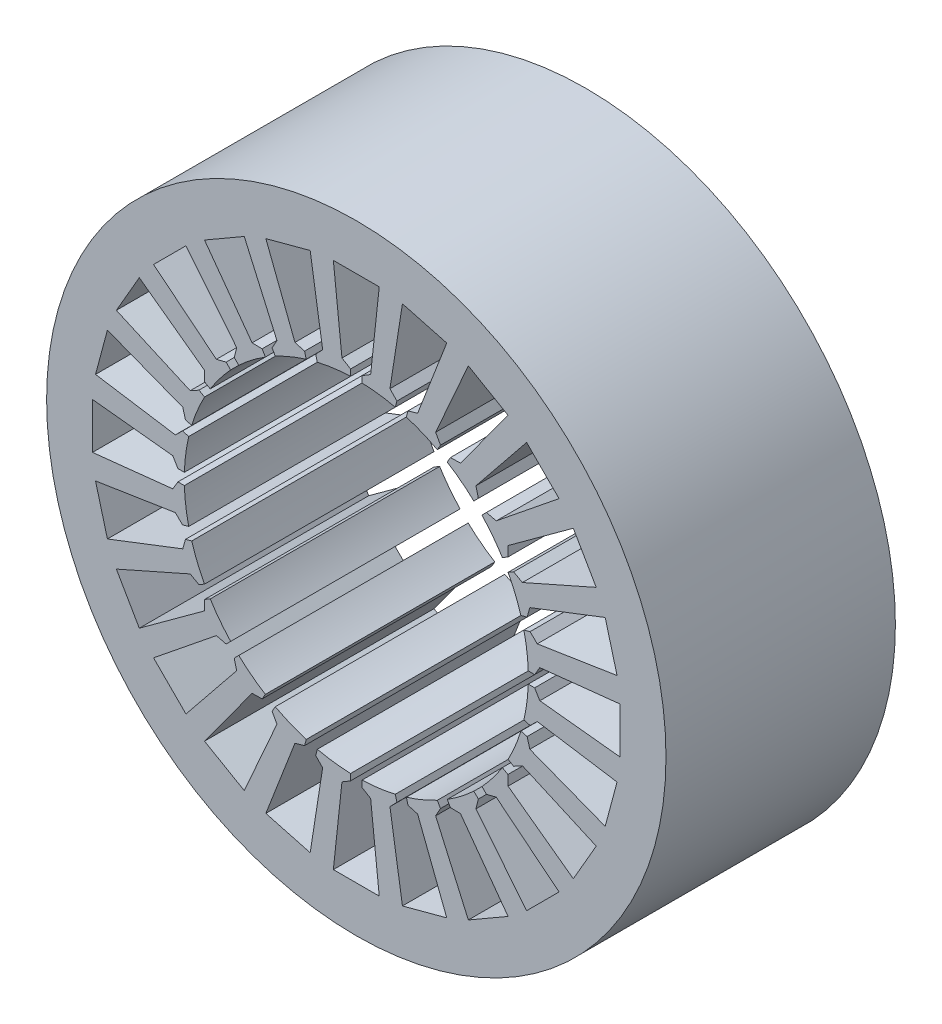
SolidWorks part; units mm, degrees
ref_plane "Спереди" through (0, 0, 0) normal (0, 0, 1) x (1, 0, 0)
ref_plane "Сверху" through (0, 0, 0) normal (0, 1, 0) x (1, 0, 0)
ref_plane "Справа" through (0, 0, 0) normal (1, 0, 0) x (0, 0, -1)
sketch "Эскиз1" plane through (0, 0, 0) normal (0, 0, 1) x (1, 0, 0)
  circle A0 centre (0, 0) radius 54
  circle A1 centre (0, 0) radius 30
extrude "Stator_stack" add sketch "Эскиз1" along normal blind 40 from offset 20
sketch "Эскиз2" plane through (0, 0, 0) normal (0, 0, 1) x (1, 0, 0)
  line L0 (28.9828, -1) -> (31.1, -1)
  line L1 (31.1, -1) -> (32, -2.5)
  line L2 (32, -2.5) -> (39.5, -3.3036)
  line L3 (39.5, -3.3036) -> (46, -4)
  line L4 (46, -4) -> (46, 4)
  line L5 (46, 4) -> (39.5, 3.3036)
  line L6 (39.5, 3.3036) -> (32, 2.5)
  line L7 (32, 2.5) -> (31.1, 1)
  line L8 (31.1, 1) -> (28.9828, 1)
  line L9 (28.9828, 1) -> (28.9828, -1)
  line L10 (28.254, 6.5354) -> (30.2991, 7.0833)
  line L11 (30.2991, 7.0833) -> (31.5567, 5.8674)
  line L12 (31.5567, 5.8674) -> (39.0091, 7.0323)
  line L13 (39.0091, 7.0323) -> (45.4679, 8.042)
  line L14 (45.4679, 8.042) -> (43.3973, 15.7694)
  line L15 (43.3973, 15.7694) -> (37.299, 13.4144)
  line L16 (37.299, 13.4144) -> (30.2626, 10.697)
  line L17 (30.2626, 10.697) -> (29.7815, 9.0152)
  line L18 (29.7815, 9.0152) -> (27.7364, 8.4672)
  line L19 (27.7364, 8.4672) -> (28.254, 6.5354)
  line L20 (25.5998, 13.6254) -> (27.4334, 14.684)
  line L21 (27.4334, 14.684) -> (28.9628, 13.8349)
  line L22 (28.9628, 13.8349) -> (35.8598, 16.889)
  line L23 (35.8598, 16.889) -> (41.8372, 19.5359)
  line L24 (41.8372, 19.5359) -> (37.8372, 26.4641)
  line L25 (37.8372, 26.4641) -> (32.5562, 22.611)
  line L26 (32.5562, 22.611) -> (26.4628, 18.1651)
  line L27 (26.4628, 18.1651) -> (26.4334, 16.416)
  line L28 (26.4334, 16.416) -> (24.5998, 15.3574)
  line L29 (24.5998, 15.3574) -> (25.5998, 13.6254)
  line L30 (21.201, 19.7868) -> (22.6981, 21.2839)
  line L31 (22.6981, 21.2839) -> (24.3952, 20.8597)
  line L32 (24.3952, 20.8597) -> (30.2667, 25.5947)
  line L33 (30.2667, 25.5947) -> (35.3553, 29.6985)
  line L34 (35.3553, 29.6985) -> (29.6985, 35.3553)
  line L35 (29.6985, 35.3553) -> (25.5947, 30.2667)
  line L36 (25.5947, 30.2667) -> (20.8597, 24.3952)
  line L37 (20.8597, 24.3952) -> (21.2839, 22.6981)
  line L38 (21.2839, 22.6981) -> (19.7868, 21.201)
  line L39 (19.7868, 21.201) -> (21.201, 19.7868)
  line L40 (15.3574, 24.5998) -> (16.416, 26.4334)
  line L41 (16.416, 26.4334) -> (18.1651, 26.4628)
  line L42 (18.1651, 26.4628) -> (22.611, 32.5562)
  line L43 (22.611, 32.5562) -> (26.4641, 37.8372)
  line L44 (26.4641, 37.8372) -> (19.5359, 41.8372)
  line L45 (19.5359, 41.8372) -> (16.889, 35.8598)
  line L46 (16.889, 35.8598) -> (13.8349, 28.9628)
  line L47 (13.8349, 28.9628) -> (14.684, 27.4334)
  line L48 (14.684, 27.4334) -> (13.6254, 25.5998)
  line L49 (13.6254, 25.5998) -> (15.3574, 24.5998)
  line L50 (8.4672, 27.7364) -> (9.0152, 29.7815)
  line L51 (9.0152, 29.7815) -> (10.697, 30.2626)
  line L52 (10.697, 30.2626) -> (13.4144, 37.299)
  line L53 (13.4144, 37.299) -> (15.7694, 43.3973)
  line L54 (15.7694, 43.3973) -> (8.042, 45.4679)
  line L55 (8.042, 45.4679) -> (7.0323, 39.0091)
  line L56 (7.0323, 39.0091) -> (5.8674, 31.5567)
  line L57 (5.8674, 31.5567) -> (7.0833, 30.2991)
  line L58 (7.0833, 30.2991) -> (6.5354, 28.254)
  line L59 (6.5354, 28.254) -> (8.4672, 27.7364)
  line L60 (1, 28.9828) -> (1, 31.1)
  line L61 (1, 31.1) -> (2.5, 32)
  line L62 (2.5, 32) -> (3.3036, 39.5)
  line L63 (3.3036, 39.5) -> (4, 46)
  line L64 (4, 46) -> (-4, 46)
  line L65 (-4, 46) -> (-3.3036, 39.5)
  line L66 (-3.3036, 39.5) -> (-2.5, 32)
  line L67 (-2.5, 32) -> (-1, 31.1)
  line L68 (-1, 31.1) -> (-1, 28.9828)
  line L69 (-1, 28.9828) -> (1, 28.9828)
  line L70 (-6.5354, 28.254) -> (-7.0833, 30.2991)
  line L71 (-7.0833, 30.2991) -> (-5.8674, 31.5567)
  line L72 (-5.8674, 31.5567) -> (-7.0323, 39.0091)
  line L73 (-7.0323, 39.0091) -> (-8.042, 45.4679)
  line L74 (-8.042, 45.4679) -> (-15.7694, 43.3973)
  line L75 (-15.7694, 43.3973) -> (-13.4144, 37.299)
  line L76 (-13.4144, 37.299) -> (-10.697, 30.2626)
  line L77 (-10.697, 30.2626) -> (-9.0152, 29.7815)
  line L78 (-9.0152, 29.7815) -> (-8.4672, 27.7364)
  line L79 (-8.4672, 27.7364) -> (-6.5354, 28.254)
  line L80 (-13.6254, 25.5998) -> (-14.684, 27.4334)
  line L81 (-14.684, 27.4334) -> (-13.8349, 28.9628)
  line L82 (-13.8349, 28.9628) -> (-16.889, 35.8598)
  line L83 (-16.889, 35.8598) -> (-19.5359, 41.8372)
  line L84 (-19.5359, 41.8372) -> (-26.4641, 37.8372)
  line L85 (-26.4641, 37.8372) -> (-22.611, 32.5562)
  line L86 (-22.611, 32.5562) -> (-18.1651, 26.4628)
  line L87 (-18.1651, 26.4628) -> (-16.416, 26.4334)
  line L88 (-16.416, 26.4334) -> (-15.3574, 24.5998)
  line L89 (-15.3574, 24.5998) -> (-13.6254, 25.5998)
  line L90 (-19.7868, 21.201) -> (-21.2839, 22.6981)
  line L91 (-21.2839, 22.6981) -> (-20.8597, 24.3952)
  line L92 (-20.8597, 24.3952) -> (-25.5947, 30.2667)
  line L93 (-25.5947, 30.2667) -> (-29.6985, 35.3553)
  line L94 (-29.6985, 35.3553) -> (-35.3553, 29.6985)
  line L95 (-35.3553, 29.6985) -> (-30.2667, 25.5947)
  line L96 (-30.2667, 25.5947) -> (-24.3952, 20.8597)
  line L97 (-24.3952, 20.8597) -> (-22.6981, 21.2839)
  line L98 (-22.6981, 21.2839) -> (-21.201, 19.7868)
  line L99 (-21.201, 19.7868) -> (-19.7868, 21.201)
  line L100 (-24.5998, 15.3574) -> (-26.4334, 16.416)
  line L101 (-26.4334, 16.416) -> (-26.4628, 18.1651)
  line L102 (-26.4628, 18.1651) -> (-32.5562, 22.611)
  line L103 (-32.5562, 22.611) -> (-37.8372, 26.4641)
  line L104 (-37.8372, 26.4641) -> (-41.8372, 19.5359)
  line L105 (-41.8372, 19.5359) -> (-35.8598, 16.889)
  line L106 (-35.8598, 16.889) -> (-28.9628, 13.8349)
  line L107 (-28.9628, 13.8349) -> (-27.4334, 14.684)
  line L108 (-27.4334, 14.684) -> (-25.5998, 13.6254)
  line L109 (-25.5998, 13.6254) -> (-24.5998, 15.3574)
  line L110 (-27.7364, 8.4672) -> (-29.7815, 9.0152)
  line L111 (-29.7815, 9.0152) -> (-30.2626, 10.697)
  line L112 (-30.2626, 10.697) -> (-37.299, 13.4144)
  line L113 (-37.299, 13.4144) -> (-43.3973, 15.7694)
  line L114 (-43.3973, 15.7694) -> (-45.4679, 8.042)
  line L115 (-45.4679, 8.042) -> (-39.0091, 7.0323)
  line L116 (-39.0091, 7.0323) -> (-31.5567, 5.8674)
  line L117 (-31.5567, 5.8674) -> (-30.2991, 7.0833)
  line L118 (-30.2991, 7.0833) -> (-28.254, 6.5354)
  line L119 (-28.254, 6.5354) -> (-27.7364, 8.4672)
  line L120 (-28.9828, 1) -> (-31.1, 1)
  line L121 (-31.1, 1) -> (-32, 2.5)
  line L122 (-32, 2.5) -> (-39.5, 3.3036)
  line L123 (-39.5, 3.3036) -> (-46, 4)
  line L124 (-46, 4) -> (-46, -4)
  line L125 (-46, -4) -> (-39.5, -3.3036)
  line L126 (-39.5, -3.3036) -> (-32, -2.5)
  line L127 (-32, -2.5) -> (-31.1, -1)
  line L128 (-31.1, -1) -> (-28.9828, -1)
  line L129 (-28.9828, -1) -> (-28.9828, 1)
  line L130 (-28.254, -6.5354) -> (-30.2991, -7.0833)
  line L131 (-30.2991, -7.0833) -> (-31.5567, -5.8674)
  line L132 (-31.5567, -5.8674) -> (-39.0091, -7.0323)
  line L133 (-39.0091, -7.0323) -> (-45.4679, -8.042)
  line L134 (-45.4679, -8.042) -> (-43.3973, -15.7694)
  line L135 (-43.3973, -15.7694) -> (-37.299, -13.4144)
  line L136 (-37.299, -13.4144) -> (-30.2626, -10.697)
  line L137 (-30.2626, -10.697) -> (-29.7815, -9.0152)
  line L138 (-29.7815, -9.0152) -> (-27.7364, -8.4672)
  line L139 (-27.7364, -8.4672) -> (-28.254, -6.5354)
  line L140 (-25.5998, -13.6254) -> (-27.4334, -14.684)
  line L141 (-27.4334, -14.684) -> (-28.9628, -13.8349)
  line L142 (-28.9628, -13.8349) -> (-35.8598, -16.889)
  line L143 (-35.8598, -16.889) -> (-41.8372, -19.5359)
  line L144 (-41.8372, -19.5359) -> (-37.8372, -26.4641)
  line L145 (-37.8372, -26.4641) -> (-32.5562, -22.611)
  line L146 (-32.5562, -22.611) -> (-26.4628, -18.1651)
  line L147 (-26.4628, -18.1651) -> (-26.4334, -16.416)
  line L148 (-26.4334, -16.416) -> (-24.5998, -15.3574)
  line L149 (-24.5998, -15.3574) -> (-25.5998, -13.6254)
  line L150 (-21.201, -19.7868) -> (-22.6981, -21.2839)
  line L151 (-22.6981, -21.2839) -> (-24.3952, -20.8597)
  line L152 (-24.3952, -20.8597) -> (-30.2667, -25.5947)
  line L153 (-30.2667, -25.5947) -> (-35.3553, -29.6985)
  line L154 (-35.3553, -29.6985) -> (-29.6985, -35.3553)
  line L155 (-29.6985, -35.3553) -> (-25.5947, -30.2667)
  line L156 (-25.5947, -30.2667) -> (-20.8597, -24.3952)
  line L157 (-20.8597, -24.3952) -> (-21.2839, -22.6981)
  line L158 (-21.2839, -22.6981) -> (-19.7868, -21.201)
  line L159 (-19.7868, -21.201) -> (-21.201, -19.7868)
  line L160 (-15.3574, -24.5998) -> (-16.416, -26.4334)
  line L161 (-16.416, -26.4334) -> (-18.1651, -26.4628)
  line L162 (-18.1651, -26.4628) -> (-22.611, -32.5562)
  line L163 (-22.611, -32.5562) -> (-26.4641, -37.8372)
  line L164 (-26.4641, -37.8372) -> (-19.5359, -41.8372)
  line L165 (-19.5359, -41.8372) -> (-16.889, -35.8598)
  line L166 (-16.889, -35.8598) -> (-13.8349, -28.9628)
  line L167 (-13.8349, -28.9628) -> (-14.684, -27.4334)
  line L168 (-14.684, -27.4334) -> (-13.6254, -25.5998)
  line L169 (-13.6254, -25.5998) -> (-15.3574, -24.5998)
  line L170 (-8.4672, -27.7364) -> (-9.0152, -29.7815)
  line L171 (-9.0152, -29.7815) -> (-10.697, -30.2626)
  line L172 (-10.697, -30.2626) -> (-13.4144, -37.299)
  line L173 (-13.4144, -37.299) -> (-15.7694, -43.3973)
  line L174 (-15.7694, -43.3973) -> (-8.042, -45.4679)
  line L175 (-8.042, -45.4679) -> (-7.0323, -39.0091)
  line L176 (-7.0323, -39.0091) -> (-5.8674, -31.5567)
  line L177 (-5.8674, -31.5567) -> (-7.0833, -30.2991)
  line L178 (-7.0833, -30.2991) -> (-6.5354, -28.254)
  line L179 (-6.5354, -28.254) -> (-8.4672, -27.7364)
  line L180 (-1, -28.9828) -> (-1, -31.1)
  line L181 (-1, -31.1) -> (-2.5, -32)
  line L182 (-2.5, -32) -> (-3.3036, -39.5)
  line L183 (-3.3036, -39.5) -> (-4, -46)
  line L184 (-4, -46) -> (4, -46)
  line L185 (4, -46) -> (3.3036, -39.5)
  line L186 (3.3036, -39.5) -> (2.5, -32)
  line L187 (2.5, -32) -> (1, -31.1)
  line L188 (1, -31.1) -> (1, -28.9828)
  line L189 (1, -28.9828) -> (-1, -28.9828)
  line L190 (6.5354, -28.254) -> (7.0833, -30.2991)
  line L191 (7.0833, -30.2991) -> (5.8674, -31.5567)
  line L192 (5.8674, -31.5567) -> (7.0323, -39.0091)
  line L193 (7.0323, -39.0091) -> (8.042, -45.4679)
  line L194 (8.042, -45.4679) -> (15.7694, -43.3973)
  line L195 (15.7694, -43.3973) -> (13.4144, -37.299)
  line L196 (13.4144, -37.299) -> (10.697, -30.2626)
  line L197 (10.697, -30.2626) -> (9.0152, -29.7815)
  line L198 (9.0152, -29.7815) -> (8.4672, -27.7364)
  line L199 (8.4672, -27.7364) -> (6.5354, -28.254)
  line L200 (13.6254, -25.5998) -> (14.684, -27.4334)
  line L201 (14.684, -27.4334) -> (13.8349, -28.9628)
  line L202 (13.8349, -28.9628) -> (16.889, -35.8598)
  line L203 (16.889, -35.8598) -> (19.5359, -41.8372)
  line L204 (19.5359, -41.8372) -> (26.4641, -37.8372)
  line L205 (26.4641, -37.8372) -> (22.611, -32.5562)
  line L206 (22.611, -32.5562) -> (18.1651, -26.4628)
  line L207 (18.1651, -26.4628) -> (16.416, -26.4334)
  line L208 (16.416, -26.4334) -> (15.3574, -24.5998)
  line L209 (15.3574, -24.5998) -> (13.6254, -25.5998)
  line L210 (19.7868, -21.201) -> (21.2839, -22.6981)
  line L211 (21.2839, -22.6981) -> (20.8597, -24.3952)
  line L212 (20.8597, -24.3952) -> (25.5947, -30.2667)
  line L213 (25.5947, -30.2667) -> (29.6985, -35.3553)
  line L214 (29.6985, -35.3553) -> (35.3553, -29.6985)
  line L215 (35.3553, -29.6985) -> (30.2667, -25.5947)
  line L216 (30.2667, -25.5947) -> (24.3952, -20.8597)
  line L217 (24.3952, -20.8597) -> (22.6981, -21.2839)
  line L218 (22.6981, -21.2839) -> (21.201, -19.7868)
  line L219 (21.201, -19.7868) -> (19.7868, -21.201)
  line L220 (24.5998, -15.3574) -> (26.4334, -16.416)
  line L221 (26.4334, -16.416) -> (26.4628, -18.1651)
  line L222 (26.4628, -18.1651) -> (32.5562, -22.611)
  line L223 (32.5562, -22.611) -> (37.8372, -26.4641)
  line L224 (37.8372, -26.4641) -> (41.8372, -19.5359)
  line L225 (41.8372, -19.5359) -> (35.8598, -16.889)
  line L226 (35.8598, -16.889) -> (28.9628, -13.8349)
  line L227 (28.9628, -13.8349) -> (27.4334, -14.684)
  line L228 (27.4334, -14.684) -> (25.5998, -13.6254)
  line L229 (25.5998, -13.6254) -> (24.5998, -15.3574)
  line L230 (27.7364, -8.4672) -> (29.7815, -9.0152)
  line L231 (29.7815, -9.0152) -> (30.2626, -10.697)
  line L232 (30.2626, -10.697) -> (37.299, -13.4144)
  line L233 (37.299, -13.4144) -> (43.3973, -15.7694)
  line L234 (43.3973, -15.7694) -> (45.4679, -8.042)
  line L235 (45.4679, -8.042) -> (39.0091, -7.0323)
  line L236 (39.0091, -7.0323) -> (31.5567, -5.8674)
  line L237 (31.5567, -5.8674) -> (30.2991, -7.0833)
  line L238 (30.2991, -7.0833) -> (28.254, -6.5354)
  line L239 (28.254, -6.5354) -> (27.7364, -8.4672)
extrude "Stator_slots" cut sketch "Эскиз2" against normal mid plane 42
